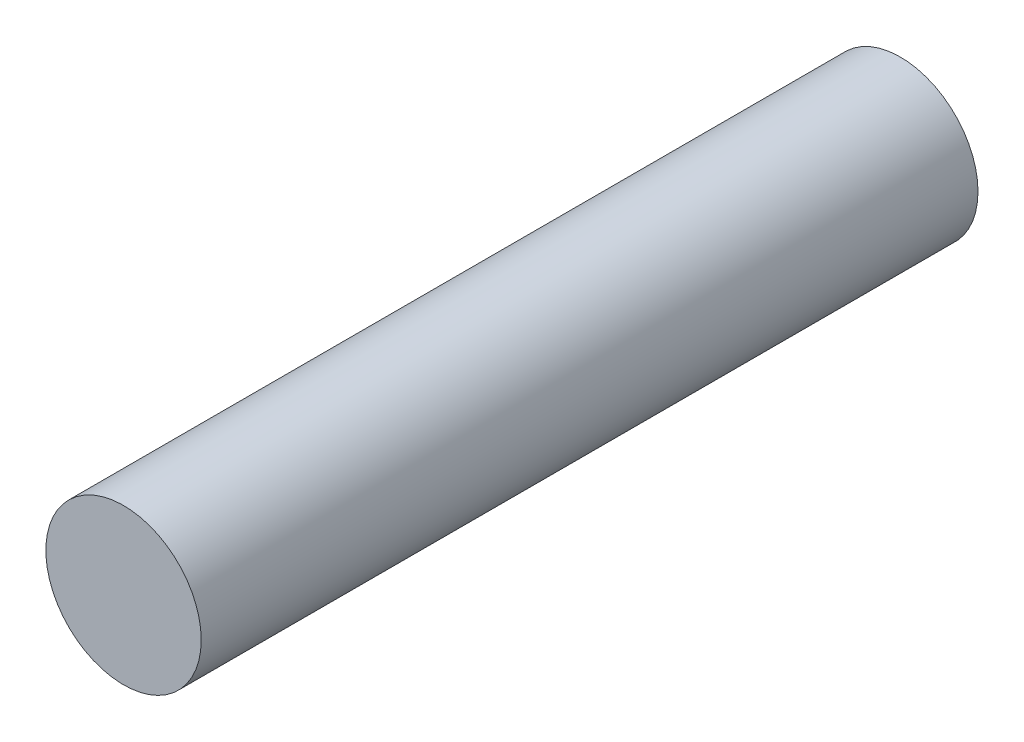
SolidWorks part; units mm, degrees
ref_plane "Front Plane" through (0, 0, 0) normal (0, 0, 1) x (1, 0, 0)
ref_plane "Top Plane" through (0, 0, 0) normal (0, 1, 0) x (1, 0, 0)
ref_plane "Right Plane" through (0, 0, 0) normal (1, 0, 0) x (0, 0, -1)
sketch "Sketch1" plane through (0, 0, 0) normal (0, 0, 1) x (1, 0, 0)
  line L1 (0, 0) -> (0, 621.8565) construction
  circle A0 centre (0, 0) radius 100
extrude "Boss-Extrude1" add sketch "Sketch1" along normal blind 1000
